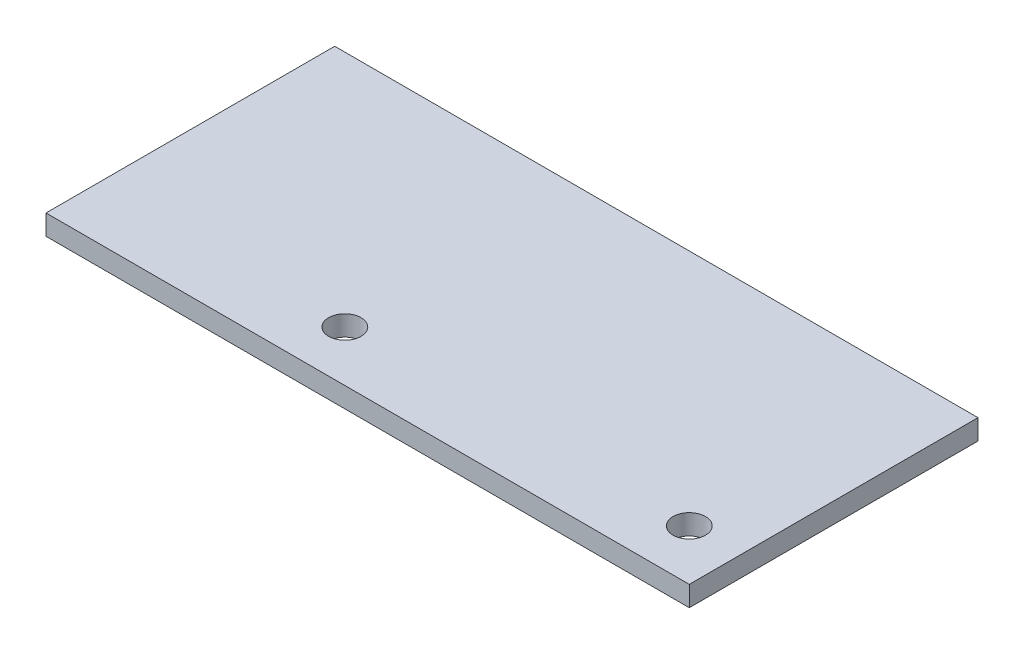
SolidWorks part; units mm, degrees
ref_plane "Front Plane" through (0, 0, 0) normal (0, 0, 1) x (1, 0, 0)
ref_plane "Top Plane" through (0, 0, 0) normal (0, 1, 0) x (1, 0, 0)
ref_plane "Right Plane" through (0, 0, 0) normal (1, 0, 0) x (0, 0, -1)
sketch "Sketch1" plane through (0, 0, 0) normal (0, 1, 0) x (1, 0, 0)
  line L1 (0, 0) -> (63.5, 0)
  line L2 (0, 0) -> (0, 28.5)
  line L3 (0, 28.5) -> (63.5, 28.5)
  line L4 (63.5, 0) -> (63.5, 28.5)
  circle A0 centre (58.5, 5) radius 1.6
  circle A1 centre (24.5, 5) radius 1.6
  dimension "D1" = 63.5
  dimension "D2" = 28.5
  dimension "D3" = 5
  dimension "D4" = 5
  dimension "D5" = 2
extrude "Boss-Extrude1" add sketch "Sketch1" along normal blind 2
